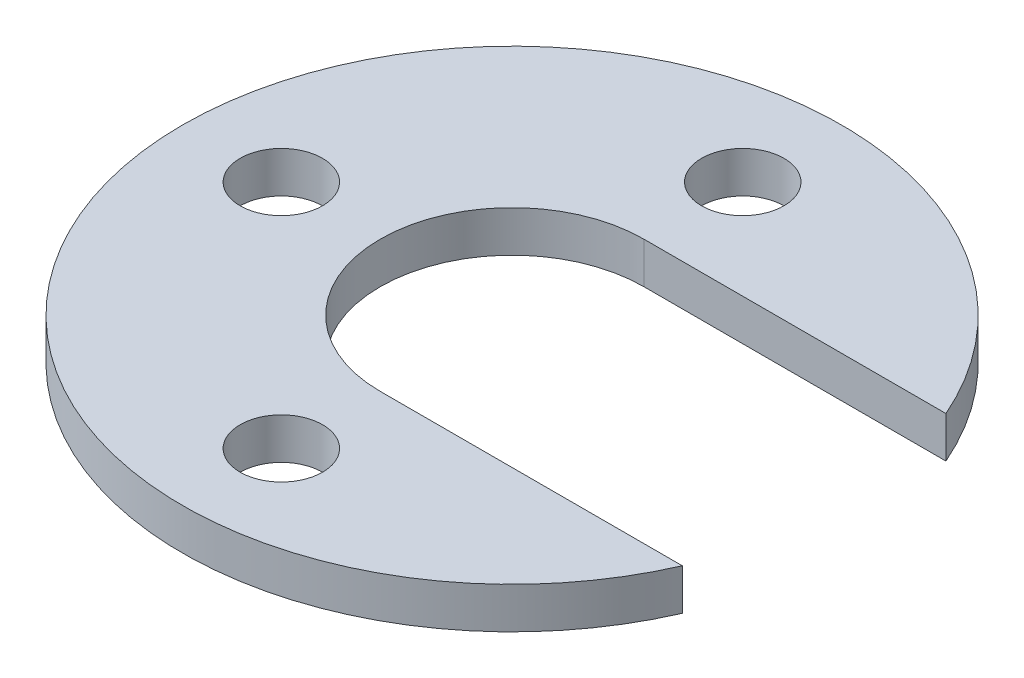
SolidWorks part; units mm, degrees
ref_plane "Front Plane" through (0, 0, 0) normal (0, 0, 1) x (1, 0, 0)
ref_plane "Top Plane" through (0, 0, 0) normal (0, 1, 0) x (1, 0, 0)
ref_plane "Right Plane" through (0, 0, 0) normal (1, 0, 0) x (0, 0, -1)
sketch "Sketch1" plane through (0, 0, 0) normal (0, 1, 0) x (1, 0, 0)
  line L0 (-61.5309, 0) -> (61.5309, 0) construction
  line L1 (0, 60.2557) -> (0, -60.2557) construction
  line L2 (0, 16) -> (36.6606, 16)
  line L3 (0, -16) -> (36.6606, -16)
  arc A0 (36.6606, 16) -> (36.6606, -16) centre (0, 0) ccw
  circle A1 centre (0, 28) radius 5
  circle A3 centre (0, -28) radius 5
  circle A4 centre (-28, 0) radius 5
  circle A5 centre (28, 0) radius 5 [skipped]
  arc A6 (0, 16) -> (0, -16) centre (0, 0) ccw
  point P5 (0, 0)
  point P9 (0, 0)
  point P19 (0, 0)
  dimension "D1" = 80
  dimension "D3" = 5
  dimension "D5" = 32
  dimension "D2" = 28
  dimension "D4" = 4
extrude "Boss-Extrude1" add sketch "Sketch1" along normal blind 5
